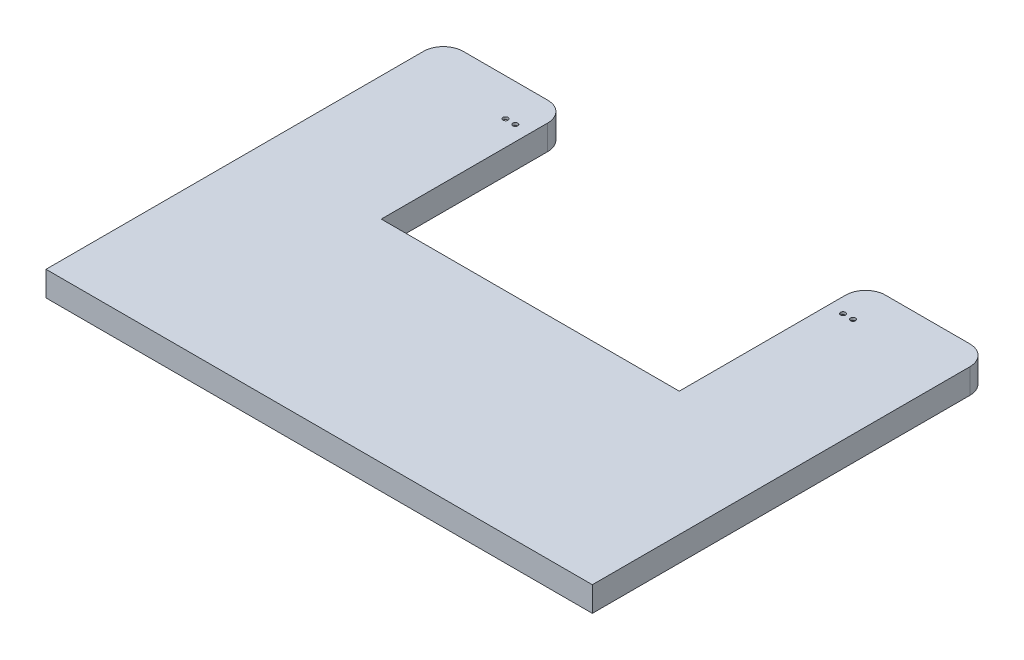
SolidWorks part; units mm, degrees
material "ABS"
ref_plane "Front Plane" through (0, 0, 0) normal (0, 0, 1) x (1, 0, 0)
ref_plane "Top Plane" through (0, 0, 0) normal (0, 1, 0) x (1, 0, 0)
ref_plane "Right Plane" through (0, 0, 0) normal (1, 0, 0) x (0, 0, -1)
sketch "Sketch1" plane through (0, 0, 0) normal (0, 1, 0) x (1, 0, 0)
  line L1 (-279.4, -203.2) -> (279.4, -203.2)
  line L2 (-279.4, -203.2) -> (-279.4, 203.2)
  line L3 (-279.4, 203.2) -> (279.4, 203.2)
  line L4 (279.4, -203.2) -> (279.4, 203.2)
  line L5 (-279.4, -203.2) -> (279.4, 203.2) construction
  line L6 (-279.4, 203.2) -> (279.4, -203.2) construction
  line L7 (-152.4, 203.2) -> (152.4, 203.2)
  line L8 (-152.4, 203.2) -> (-152.4, 12.7)
  line L9 (-152.4, 12.7) -> (152.4, 12.7)
  line L10 (152.4, 203.2) -> (152.4, 12.7)
  point P0 (0, 0)
  dimension "D1" = 558.8
  dimension "D2" = 406.4
  dimension "D3" = 127
  dimension "D4" = 127
  dimension "D5" = 190.5
extrude "Boss-Extrude1" add sketch "Sketch1" along normal blind 25.4 contours L3 L10 L9 L8 L2 L1 L4
fillet "Fillet1" radius 20.32 4 edges at (279.4, 12.7, -203.2) (152.4, 12.7, -203.2) (-279.4, 12.7, -203.2) (-152.4, 12.7, -203.2)
shell "Shell1" thickness 2.54
sketch "Sketch2" plane through (0, 25.4, 0) normal (0, 1, 0) x (1, 0, 0)
  line L0 (-317.2722, 165.1) -> (360.7838, 165.1) construction
  line L1 (-279.4, -203.2) -> (279.4, -203.2) construction
  line L2 (152.4, 182.88) -> (152.4, 12.7) construction
  line L3 (-152.4, 182.88) -> (-152.4, 12.7) construction
  circle A0 centre (-177.72, 165.1) radius 2.54
  circle A1 centre (-167.56, 165.1) radius 2.54
  circle A2 centre (167.56, 165.1) radius 2.54
  circle A3 centre (177.72, 165.1) radius 2.54
  point P12 (157.4, 165.1)
  point P13 (-157.4, 165.1)
  dimension "D2" = 10.16
  dimension "D8" = 5.08
  dimension "D1" = 368.3
  dimension "D3" = 10.16
  dimension "D4" = 10.16
  dimension "D5" = 10.16
  dimension "D6" = 5
  dimension "D7" = 5
extrude "Cut-Extrude1" cut sketch "Sketch2" against normal through all
